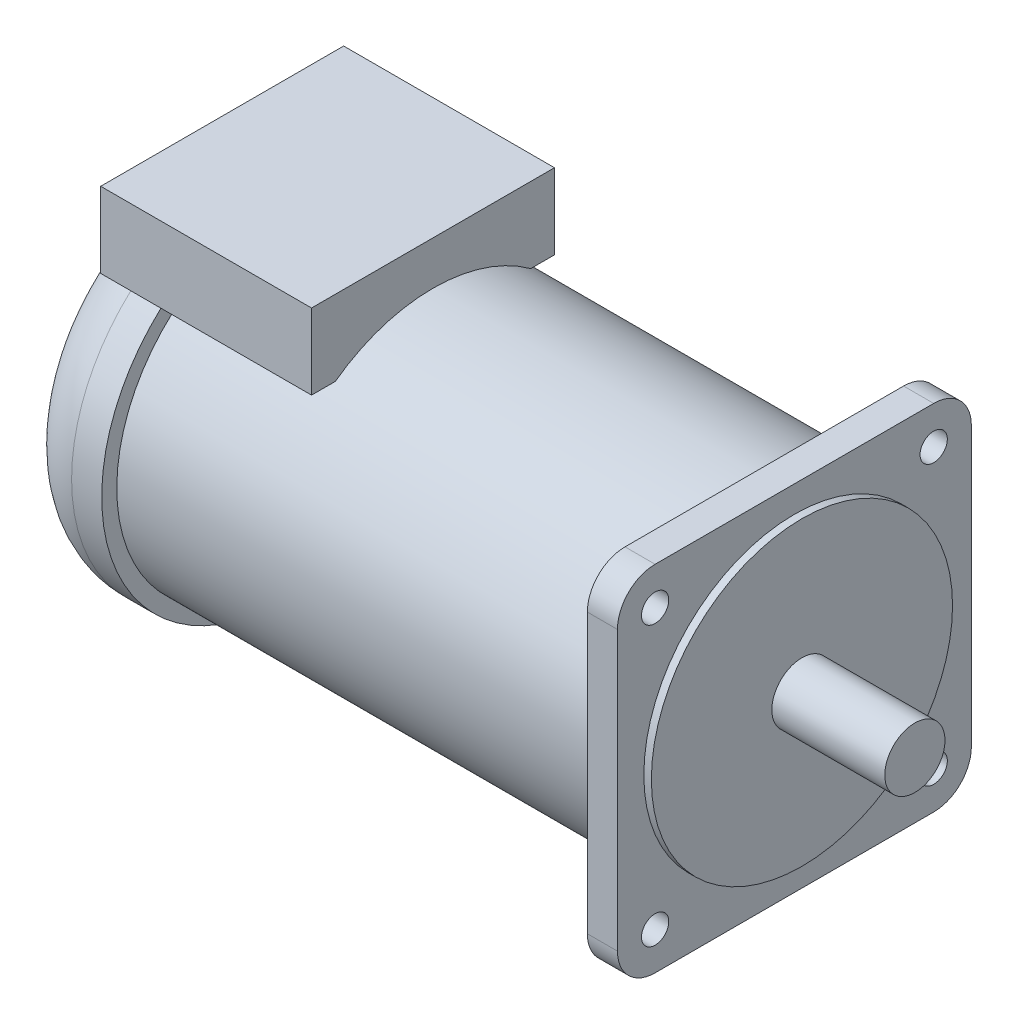
SolidWorks part; units mm, degrees
material "PW50:30:C1:0:1:2:Re:10:"
ref_plane "front" through (0, 0, 0) normal (0, 0, 1) x (1, 0, 0)
ref_plane "top" through (0, 0, 0) normal (0, 1, 0) x (1, 0, 0)
ref_plane "side" through (0, 0, 0) normal (1, 0, 0) x (0, 0, -1)
sketch "Sketch1" plane through (0, 0, 0) normal (0, 0, 1) x (1, 0, 0)
  line L0 (0, 0) -> (63.4876, 0) construction
  line L1 (0, 0) -> (0, 12.7)
  line L2 (0, 12.7) -> (-50.8, 12.7)
  line L3 (-50.8, 12.7) -> (-50.8, 69.85)
  line L6 (-50.8, 69.85) -> (-266.7, 69.85)
  line L7 (-266.7, 69.85) -> (-266.7, 76.2)
  line L8 (-266.7, 76.2) -> (-279.4, 76.2)
  line L9 (-304.8, 50.8) -> (-304.8, 0)
  line L10 (-304.8, 0) -> (0, 0)
  arc A0 (-279.4, 76.2) -> (-304.8, 50.8) centre (-279.4, 50.8) ccw
  dimension "D3" = 25.4
  dimension "D1" = 69.85
  dimension "D2" = 76.2
  dimension "D4" = 38.1
  dimension "D5" = 254
  dimension "D6" = 50.8
  dimension "D7" = 25.4
revolve "Base-Revolve" add sketch "Sketch1" angle 360 about L0
sketch "Sketch2" plane through (-50.8, 0, 0) normal (1, 0, 0) x (0, 0, -1)
  line L0 (0, 0) -> (0, 105.8986) construction
  line L1 (0, 0) -> (105.8986, 0) construction
  line L2 (74.6125, -58.7375) -> (74.6125, 58.7375)
  line L3 (58.7375, 74.6125) -> (-58.7375, 74.6125)
  line L4 (-74.6125, -58.7375) -> (-74.6125, 58.7375)
  line L5 (58.7375, -74.6125) -> (-58.7375, -74.6125)
  arc A0 (74.6125, 58.7375) -> (58.7375, 74.6125) centre (58.7375, 58.7375) ccw
  arc A1 (-74.6125, 58.7375) -> (-58.7375, 74.6125) centre (-58.7375, 58.7375) cw
  arc A2 (-74.6125, -58.7375) -> (-58.7375, -74.6125) centre (-58.7375, -58.7375) ccw
  arc A3 (74.6125, -58.7375) -> (58.7375, -74.6125) centre (58.7375, -58.7375) cw
  point P10 (0, 74.6125)
  point P11 (74.6125, 0)
  point P18 (-74.6125, 0)
  point P19 (0, -74.6125)
  dimension "D1" = 15.875
  dimension "D2" = 149.225
extrude "Boss-Extrude1" add sketch "Sketch2" against normal blind 12.7
ref_plane "Plane4" through (-203.2, 0, 0) normal (1, 0, 0) x (0, 0, -1)
sketch "Sketch3" plane through (-203.2, 0, 0) normal (1, 0, 0) x (0, 0, -1)
  line L0 (0, 0) -> (0, 88.2412) construction
  line L1 (-51.2239, 88.2412) -> (51.2239, 88.2412)
  line L2 (-51.2239, 88.2412) -> (-51.2239, 56.4141)
  line L3 (51.2239, 56.4141) -> (-51.2239, 56.4141)
  line L4 (51.2239, 56.4141) -> (51.2239, 88.2412)
  circle A0 centre (0, 0) radius 76.2 construction
extrude "Boss-Extrude2" add sketch "Sketch3" against normal blind 88.9
sketch "Sketch4" plane through (-50.8, 0, 0) normal (1, 0, 0) x (0, 0, -1)
  circle A0 centre (0, 0) radius 63.5
  dimension "D1" = 127
extrude "pilot dia" add sketch "Sketch4" along normal blind 3.175
hole_wizard "1/2-20 Tapped Hole2" positions "Sketch6" profile "Sketch5" tap size "1/2-20" standard "Ansi Inch" end condition through all
sketch "Sketch6" plane through (-63.5, 0, 0) normal (-1, 0, 0) x (0, 0, 1)
  point P0 (58.7375, 58.7375)
sketch "Sketch5" plane through (-63.5, 58.7375, 58.7375) normal (0, 1, 0) x (0, 0, 1)
  line L0 (0, 0) -> (0, 63.5)
  line L1 (0, 63.5) -> (5.7544, 63.5)
  line L2 (5.7544, 63.5) -> (5.7544, 0)
  line L5 (5.7544, 0) -> (0, 0)
  line L11 (0, -6.35) -> (0, 107.95) construction
  dimension "Thru Hole Dia." = 11.5087
  dimension "Thru Hole Depth" = 63.5
cosmetic thread "Cosmetic Thread1" parameters "D1"=12.7, "D2"=12.7
pattern_circular "CirPattern2" count 4 over 360 about axis through (0, 0, 0) along (1, 0, 0) of "1/2-20 Tapped Hole2"
